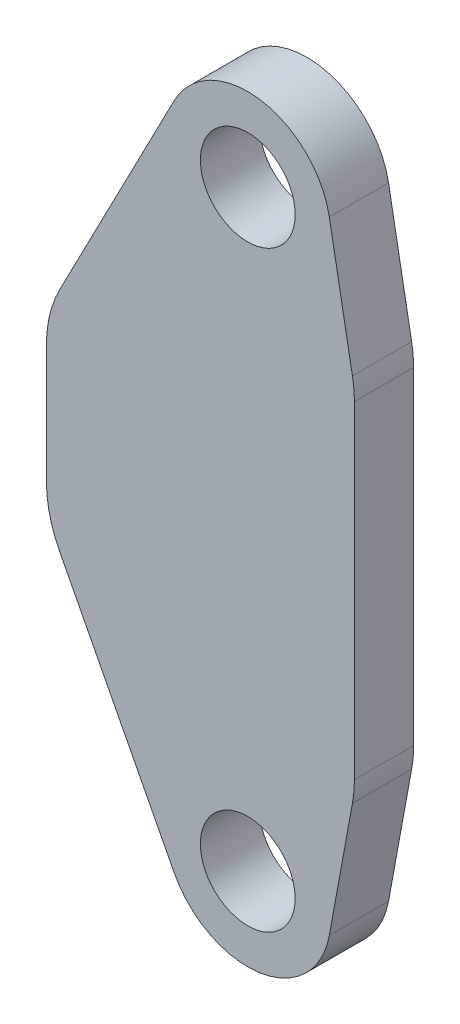
SolidWorks part; units mm, degrees
ref_plane "Front Plane" through (0, 0, 0) normal (0, 0, 1) x (1, 0, 0)
ref_plane "Top Plane" through (0, 0, 0) normal (0, 1, 0) x (1, 0, 0)
ref_plane "Right Plane" through (0, 0, 0) normal (1, 0, 0) x (0, 0, -1)
sketch "Sketch1" plane through (0, 0, 0) normal (0, 0, 1) x (1, 0, 0)
  line L0 (0, 0) -> (23, 0) construction
  line L10 (-6.2147, 28.2213) -> (-15.8782, 9.5782)
  line L11 (-17, 4.9762) -> (-17, -4.9762)
  line L16 (6.8852, 26.2626) -> (8.836, 15.6248)
  line L17 (9, 13.821) -> (9, -13.821)
  line L19 (-6.2147, -28.2213) -> (-15.8782, -9.5782)
  line L21 (6.8852, -26.2626) -> (8.836, -15.6248)
  circle A14 centre (0, 25) radius 4
  circle A15 centre (0, -25) radius 4
  circle A16 centre (0, 25) radius 7
  circle A17 centre (0, -25) radius 7
  arc A18 (-15.8782, 9.5782) -> (-17, 4.9762) centre (-7, 4.9762) ccw
  arc A19 (8.836, 15.6248) -> (9, 13.821) centre (-1, 13.821) cw
  arc A20 (-15.8782, -9.5782) -> (-17, -4.9762) centre (-7, -4.9762) cw
  arc A21 (8.836, -15.6248) -> (9, -13.821) centre (-1, -13.821) ccw
  point P13 (-17, 0)
  point P21 (9, 0)
  dimension "D2" = 10
  dimension "D3" = 26
  dimension "D10" = 8
  dimension "D4" = 50
  dimension "D5" = 9
  dimension "D11" = 3
extrude "Boss-Extrude1" add sketch "Sketch1" along normal blind 5
sketch "Sketch2" plane through (0, 0, 5) normal (0, 0, 1) x (1, 0, 0)
  line L0 (-0.093, 2.9765) -> (5.3019, 2.9765)
  line L1 (-0.093, 2.9765) -> (-0.093, -2.9765)
  line L2 (5.3019, 2.9765) -> (5.3019, -2.9765)
  line L3 (-0.093, -2.9765) -> (5.3019, -2.9765)
  line L4 (-0.093, 2.9765) -> (5.3019, -2.9765) construction
  line L5 (5.3019, 2.9765) -> (-0.093, -2.9765) construction
  point P1 (2.6045, 0)
equation "\"in_d\"=40"
equation "\"pipe_thick\"=2"
equation "\"rod_angle\"=20"
equation "\"rod_radius\"=33.5"
equation "\"rod_diameter\"=8"
equation "\"lin_bear_h\"=24"
equation "\"screw_radius\"=40"
equation "\"screw_angle\"=50"
equation "\"lin_bearing_d\"=15"
equation "\"drill_rod_pair\"=37"
equation "\"support_rod_w\"=50"
equation "\"vertical_slider_w\"=65"
equation "\"slope_angle\"=30"
